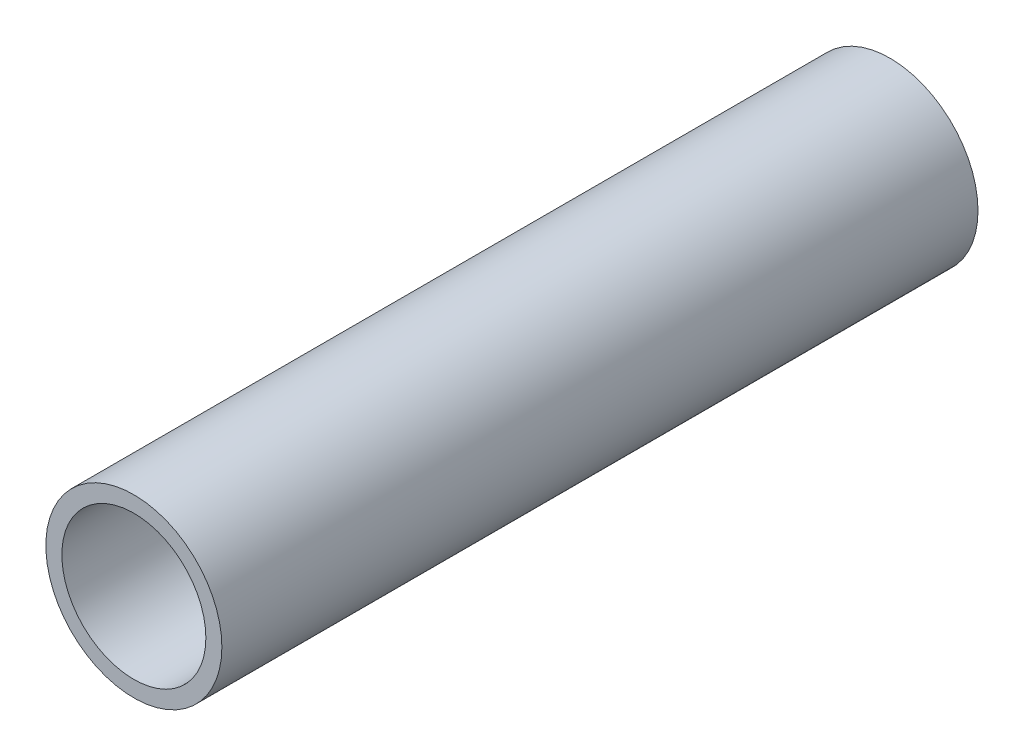
SolidWorks part; units mm, degrees
ref_plane "정면" through (0, 0, 0) normal (0, 0, 1) x (1, 0, 0)
ref_plane "윗면" through (0, 0, 0) normal (0, 1, 0) x (1, 0, 0)
ref_plane "우측면" through (0, 0, 0) normal (1, 0, 0) x (0, 0, -1)
sketch "스케치1" plane through (0, 0, 0) normal (0, 0, 1) x (1, 0, 0)
  circle A0 centre (0, 0) radius 11
  circle A1 centre (0, 0) radius 9
  dimension "D1" = 22
  dimension "D2" = 18
extrude "보스-돌출1" add sketch "스케치1" along normal blind 94.5
